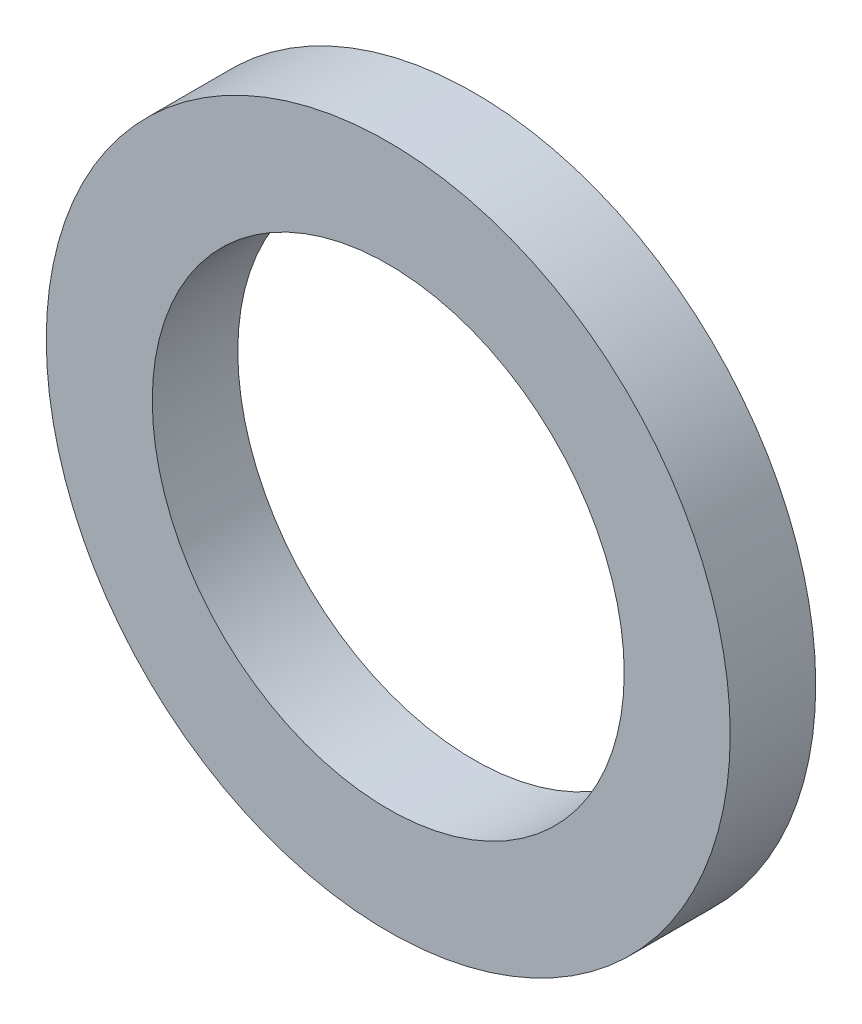
SolidWorks part; units mm, degrees
ref_plane "Front Plane" through (0, 0, 0) normal (0, 0, 1) x (1, 0, 0)
ref_plane "Top Plane" through (0, 0, 0) normal (0, 1, 0) x (1, 0, 0)
ref_plane "Right Plane" through (0, 0, 0) normal (1, 0, 0) x (0, 0, -1)
sketch "Sketch1" plane through (0, 0, 0) normal (0, 0, 1) x (1, 0, 0)
  circle A0 centre (0, 0) radius 12.7
  dimension "D1" = 25.4
extrude "Boss-Extrude1" add sketch "Sketch1" along normal blind 3.175
sketch "Sketch2" plane through (0, 0, 3.175) normal (0, 0, 1) x (1, 0, 0)
  circle A0 centre (0, 0) radius 8.763
  dimension "D1" = 17.526
extrude "Cut-Extrude1" cut sketch "Sketch2" against normal up to surface (3.175 mm away) up to face at (12.7, 0, 0)
